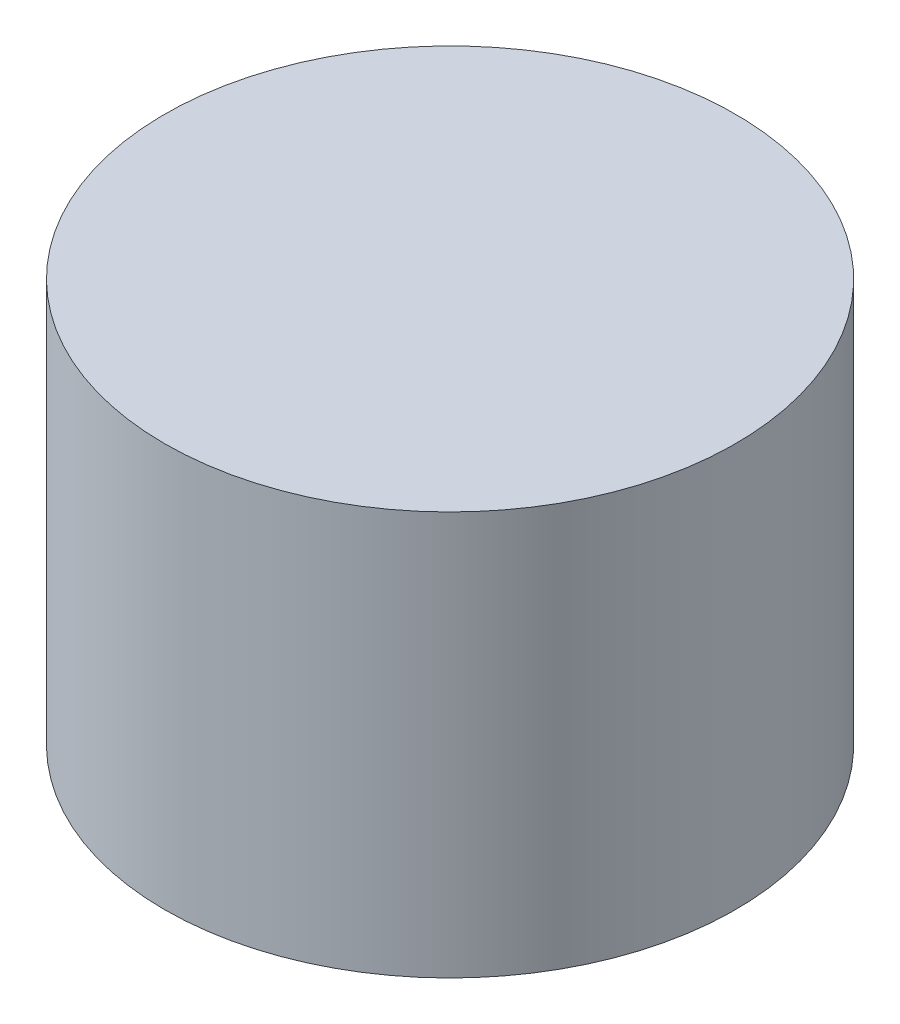
SolidWorks part; units mm, degrees
material "Aluminum Bronze"
ref_plane "Front Plane" through (0, 0, 0) normal (0, 0, 1) x (1, 0, 0)
ref_plane "Top Plane" through (0, 0, 0) normal (0, 1, 0) x (1, 0, 0)
ref_plane "Right Plane" through (0, 0, 0) normal (1, 0, 0) x (0, 0, -1)
sketch "Sketch1" plane through (0, 0, 0) normal (0, 1, 0) x (1, 0, 0)
  circle A0 centre (0, 0) radius 0.99
  dimension "D1" = 1.98
extrude "Boss-Extrude1" add sketch "Sketch1" along normal blind 1.4
